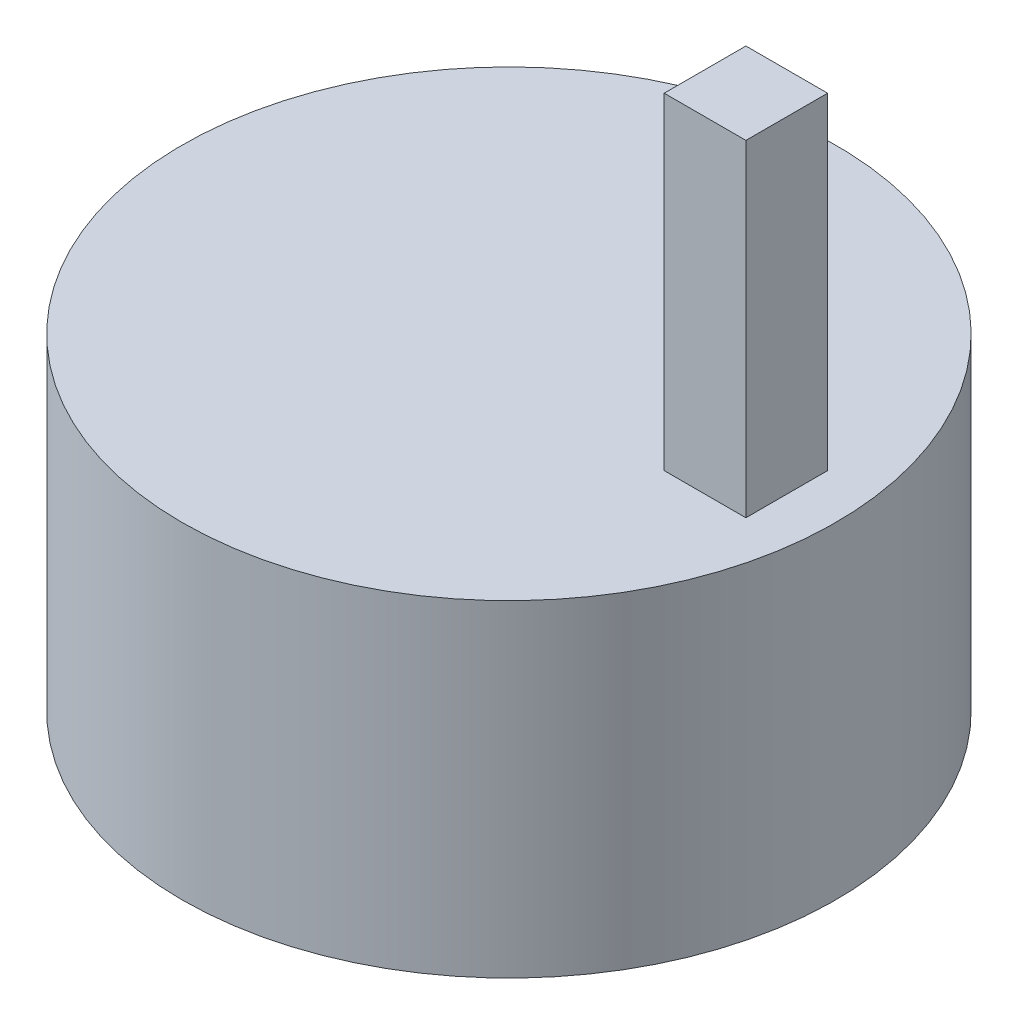
SolidWorks part; units mm, degrees
ref_plane "前视基准面" through (0, 0, 0) normal (0, 0, 1) x (1, 0, 0)
ref_plane "上视基准面" through (0, 0, 0) normal (0, 1, 0) x (1, 0, 0)
ref_plane "右视基准面" through (0, 0, 0) normal (1, 0, 0) x (0, 0, -1)
sketch "草图1" plane through (0, 0, 0) normal (0, 1, 0) x (1, 0, 0)
  circle A0 centre (0, 0) radius 20
  dimension "D1" = 40
extrude "凸台-拉伸1" add sketch "草图1" along normal blind 20
sketch "草图2" plane through (0, 20, 0) normal (0, 1, 0) x (1, 0, 0)
  line L0 (-20, 0) -> (20, 0) construction
  line L1 (12, -2.5) -> (17, -2.5)
  line L2 (12, -2.5) -> (12, 2.5)
  line L3 (12, 2.5) -> (17, 2.5)
  line L4 (17, -2.5) -> (17, 2.5)
  circle A0 centre (0, 0) radius 20 construction
  point P6 (12, 0)
  point P11 (0, 0)
  dimension "D1" = 5
  dimension "D2" = 5
  dimension "D3" = 12
extrude "凸台-拉伸2" add sketch "草图2" along normal blind 20
